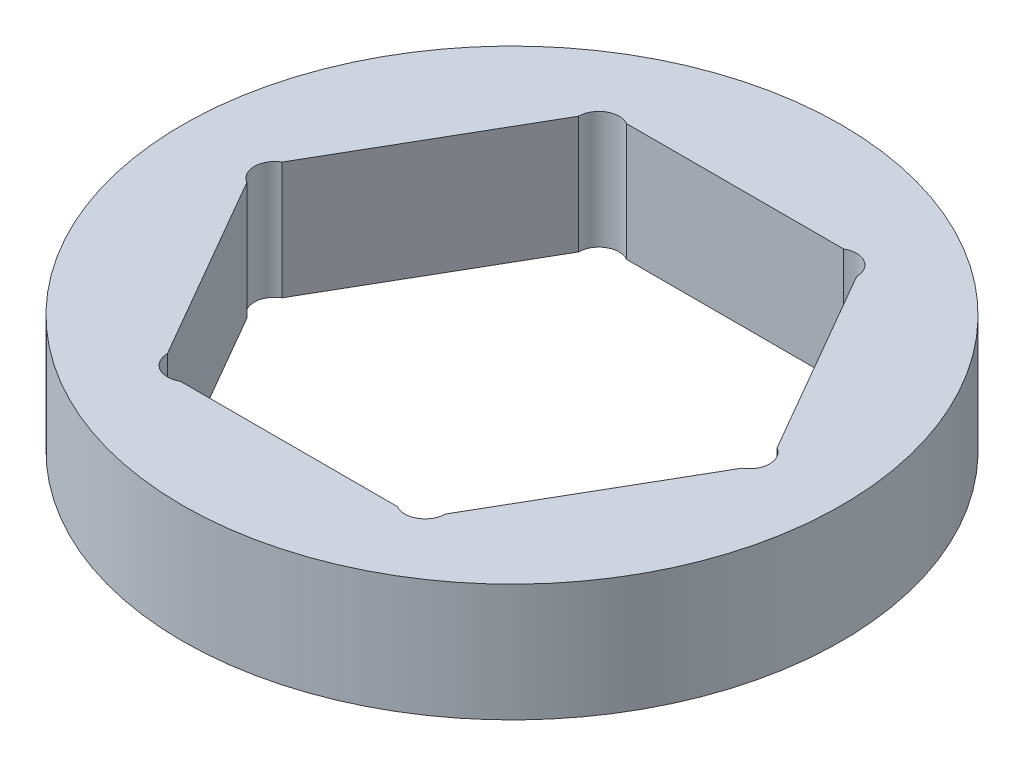
SolidWorks part; units mm, degrees
ref_plane "Front Plane" through (0, 0, 0) normal (0, 0, 1) x (1, 0, 0)
ref_plane "Top Plane" through (0, 0, 0) normal (0, 1, 0) x (1, 0, 0)
ref_plane "Right Plane" through (0, 0, 0) normal (1, 0, 0) x (0, 0, -1)
sketch "Sketch1" plane through (0, 0, 0) normal (0, 1, 0) x (1, 0, 0)
  line L0 (0, 0) -> (3.8128, 6.604) construction
  line L1 (7.6256, 0) -> (3.8128, 6.604)
  line L2 (3.8128, 6.604) -> (-3.8128, 6.604)
  line L3 (-3.8128, 6.604) -> (-7.6256, 0)
  line L4 (-7.6256, 0) -> (-3.8128, -6.604)
  line L5 (-3.8128, -6.604) -> (3.8128, -6.604)
  line L6 (3.8128, -6.604) -> (7.6256, 0)
  circle A0 centre (0, 0) radius 6.604 construction
  circle A1 centre (0, 0) radius 9.7536
  circle A2 centre (3.5128, 6.0844) radius 0.6
  circle A3 centre (7.0256, 0) radius 0.6
  circle A4 centre (3.5128, -6.0844) radius 0.6
  circle A5 centre (-3.5128, -6.0844) radius 0.6
  circle A6 centre (-7.0256, 0) radius 0.6
  circle A7 centre (-3.5128, 6.0844) radius 0.6
  point P25 (0, 0)
  dimension "D1" = 13.208
  dimension "D2" = 19.5072
  dimension "D3" = 1.2
  dimension "D4" = 6
extrude "Boss-Extrude1" add sketch "Sketch1" along normal blind 3.4798 contours A1 A7 L2 A2 L1 A3 L6 A4 L5 A5 L4 A6 L3
